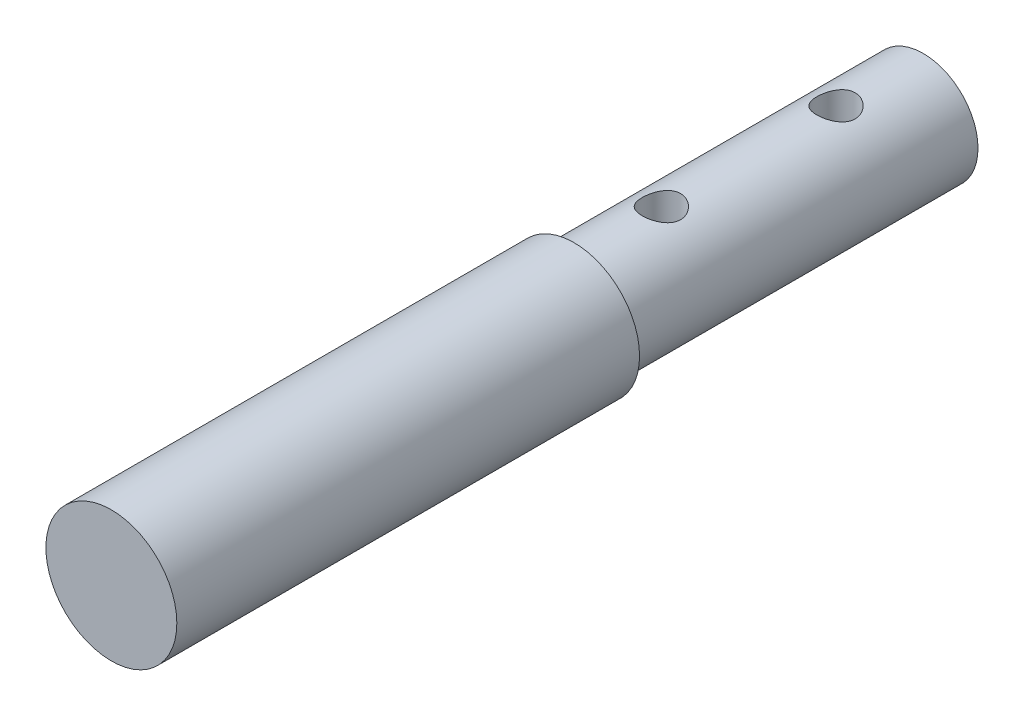
SolidWorks part; units mm, degrees
material "ASTM A36 Steel"
ref_plane "Front Plane" through (0, 0, 0) normal (0, 0, 1) x (1, 0, 0)
ref_plane "Top Plane" through (0, 0, 0) normal (0, 1, 0) x (1, 0, 0)
ref_plane "Right Plane" through (0, 0, 0) normal (1, 0, 0) x (0, 0, -1)
sketch "Sketch1" plane through (0, 0, 0) normal (0, 0, 1) x (1, 0, 0)
  circle A0 centre (0, 0) radius 31.34
  dimension "D1" = 62.68
extrude "Boss-Extrude1" add sketch "Sketch1" along normal blind 200
sketch "Sketch2" plane through (0, 0, 200) normal (0, 0, 1) x (1, 0, 0)
  circle A0 centre (0, 0) radius 37.5
  dimension "D1" = 75
extrude "Boss-Extrude2" add sketch "Sketch2" along normal blind 265
sketch "Sketch3" plane through (0, 0, 0) normal (0, 1, 0) x (1, 0, 0)
  line L0 (37.5, -200) -> (-37.5, -200) construction
  circle A0 centre (0, -150) radius 11
  circle A1 centre (0, -50) radius 11
  dimension "D1" = 22
  dimension "D3" = 100
  dimension "D4" = 22
  dimension "D2" = 50
extrude "Cut-Extrude1" cut sketch "Sketch3" against normal through all both and the other way through all
